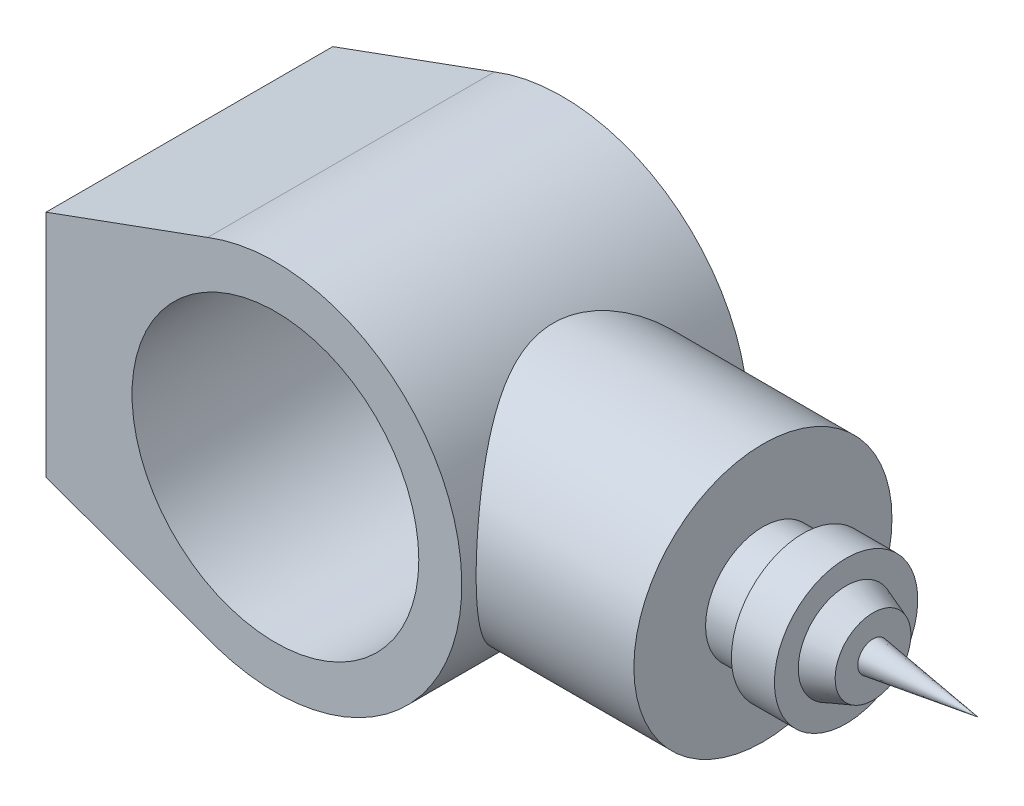
SolidWorks part; units mm, degrees
ref_plane "Front Plane" through (0, 0, 0) normal (0, 0, 1) x (1, 0, 0)
ref_plane "Top Plane" through (0, 0, 0) normal (0, 1, 0) x (1, 0, 0)
ref_plane "Right Plane" through (0, 0, 0) normal (1, 0, 0) x (0, 0, -1)
sketch "Sketch1" plane through (0, 0, 0) normal (0, 0, 1) x (1, 0, 0)
  line L0 (-80, -40) -> (-80, 40)
  line L1 (-80, 40) -> (-23.6316, 60.552)
  line L2 (-80, -40) -> (-20.4555, -61.6974)
  arc A0 (-20.4555, -61.6974) -> (-23.6316, 60.552) centre (0, 0) ccw
  circle A1 centre (0, 0) radius 50
  point P7 (-80, 0)
  dimension "D1" = 130
  dimension "D2" = 100
  dimension "D3" = 80
  dimension "D4" = 80
extrude "Boss-Extrude1" add sketch "Sketch1" along normal mid plane 100
ref_plane "Plane1" through (120, 0, 0) normal (-1, 0, 0) x (0, 0, 1)
sketch "Sketch3" plane through (120, 0, 0) normal (-1, 0, 0) x (0, 0, 1)
  circle A0 centre (0, 0) radius 45
extrude "Boss-Extrude2" add sketch "Sketch3" along normal up to next
sketch "Sketch4" plane through (0, 0, 0) normal (0, 0, 1) x (1, 0, 0)
  line L0 (120, 0) -> (195, 0)
  line L1 (120, 0) -> (120, -20)
  line L2 (120, 55) -> (120, -55) construction
  line L3 (120, -20) -> (134, -20)
  line L4 (134, -20) -> (134, -25)
  line L5 (134, -25) -> (149, -25)
  line L6 (149, -25) -> (149, -16.6672)
  line L7 (149, -16.6672) -> (158.3818, -13.2058)
  line L8 (158.3818, -13.2058) -> (158.3818, -5.3018)
  line L9 (158.3818, -5.3018) -> (195, 0)
  dimension "D1" = 20
  dimension "D2" = 14
  dimension "D3" = 15
  dimension "D4" = 5
  dimension "D5" = 10
  dimension "D6" = 37
  dimension "D7" = 75
revolve "Revolve1" add sketch "Sketch4" angle 360 about L0
